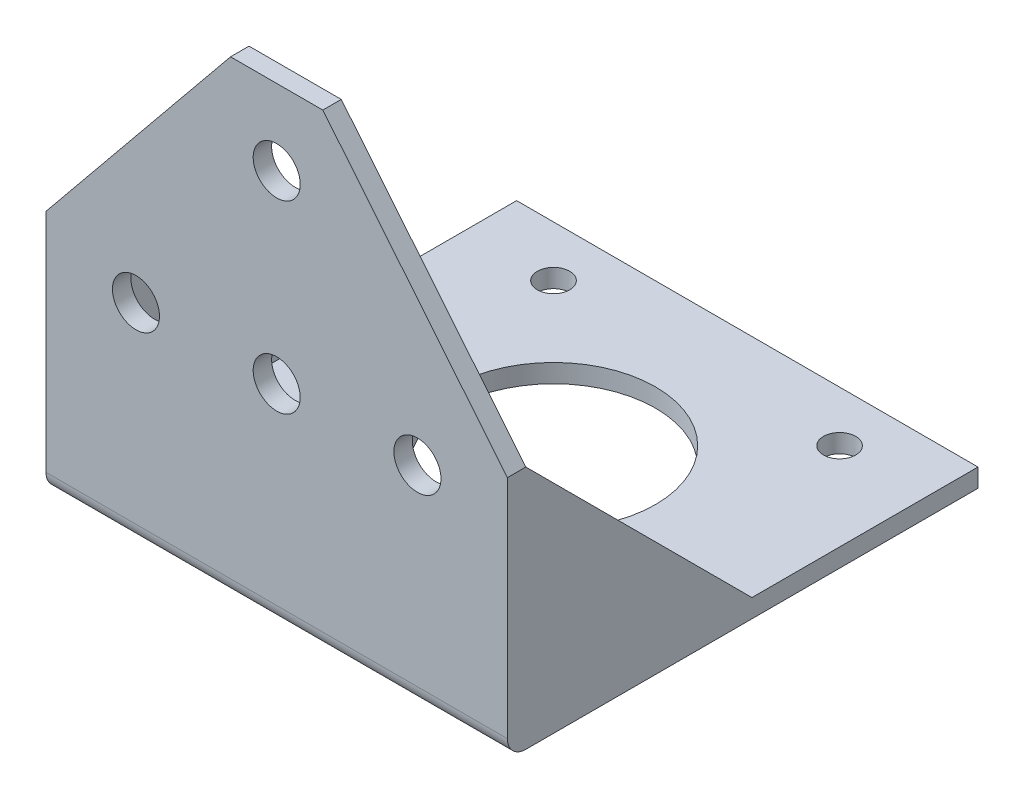
SolidWorks part; units mm, degrees
ref_plane "Front Plane" through (0, 0, 0) normal (0, 0, 1) x (1, 0, 0)
ref_plane "Top Plane" through (0, 0, 0) normal (0, 1, 0) x (1, 0, 0)
ref_plane "Right Plane" through (0, 0, 0) normal (1, 0, 0) x (0, 0, -1)
sketch "Sketch1" plane through (0, 0, 0) normal (0, 1, 0) x (1, 0, 0)
  line L0 (0, 0) -> (0, -30) construction
  line L2 (-25, 21) -> (25, 21)
  line L3 (-25, 21) -> (-25, -30)
  line L4 (-25, -30) -> (25, -30)
  line L5 (25, 21) -> (25, -30)
  line L6 (-25, 21) -> (25, -30) construction
  line L7 (-25, -30) -> (25, 21) construction
  point P2 (0, -4.5)
  dimension "D1" = 30
  dimension "D2" = 0
  dimension "D3" = 51
  dimension "D4" = 50
extrude "Boss-Extrude1" add sketch "Sketch1" along normal blind 2
sketch "Sketch2" plane through (0, 2, 0) normal (0, 1, 0) x (1, 0, 0)
  line L1 (0, 21) -> (0, -30) construction
  line L2 (25, 21) -> (-25, 21) construction
  line L3 (-25, -30) -> (25, -30) construction
  circle A0 centre (0, 0) radius 11.05
  circle A1 centre (-15.5, 15.5) radius 1.75
  circle A2 centre (-15.5, -15.5) radius 1.75
  circle A3 centre (15.5, -15.5) radius 1.75
  circle A4 centre (15.5, 15.5) radius 1.75
  dimension "D1" = 22.1
  dimension "D2" = 15.5
  dimension "D3" = 15.5
  dimension "D4" = 3.5
  dimension "D5" = 15.5
  dimension "D6" = 15.5
  dimension "D7" = 3.5
extrude "Cut-Extrude1" cut sketch "Sketch2" against normal blind 3
sketch "Sketch4" plane through (0, 2, 0) normal (0, 1, 0) x (1, 0, 0)
  line L0 (25, -30) -> (25, 21) construction
  line L1 (-25, -30) -> (25, -30)
  line L2 (-25, -30) -> (-25, -28)
  line L3 (-25, -28) -> (25, -28)
  line L4 (25, -30) -> (25, -28)
  dimension "D1" = 2
extrude "Boss-Extrude2" add sketch "Sketch4" along normal blind 49
sketch "Sketch5" plane through (25, 0, 0) normal (1, 0, 0) x (0, 0, -1)
  line L0 (-28, 26.5) -> (-3.5, 2)
  line L1 (-28, 51) -> (-28, 2) construction
  line L2 (-28, 2) -> (21, 2) construction
  line L3 (-3.5, 2) -> (-28, 2)
  line L4 (-28, 2) -> (-28, 26.5)
extrude "Boss-Extrude3" add sketch "Sketch5" against normal blind 2
sketch "Sketch6" plane through (-25, 0, 0) normal (-1, 0, 0) x (0, 0, 1)
  line L0 (28, 26.5) -> (3.5, 2)
  line L1 (28, 51) -> (28, 2) construction
  line L2 (-21, 2) -> (28, 2) construction
  line L3 (3.5, 2) -> (28, 2)
  line L4 (28, 2) -> (28, 26.5)
extrude "Boss-Extrude4" add sketch "Sketch6" against normal blind 2
sketch "Sketch7" plane through (0, 0, 28) normal (0, 0, -1) x (-1, 0, 0)
  line L0 (0, 51) -> (0, 2) construction
  line L1 (-25, 51) -> (25, 51) construction
  line L2 (-23, 2) -> (23, 2) construction
  line L3 (25, 42.8) -> (-25, 42.8) construction
  line L4 (25, 51) -> (25, 26.5) construction
  line L5 (-25, 51) -> (-25, 26.5) construction
  line L6 (25, 22.8) -> (-25, 22.8) construction
  line L7 (15.25, 51) -> (15.25, 22.8) construction
  circle A2 centre (0, 22.8) radius 2.55
  circle A3 centre (0, 42.8) radius 2.55
  circle A6 centre (15.25, 22.8) radius 2.55
  circle A7 centre (15.25, 42.8) radius 2.55
  circle A8 centre (-15.25, 42.8) radius 2.55
  circle A9 centre (-15.25, 22.8) radius 2.55
  dimension "D3" = 5.1
  dimension "D4" = 5.1
  dimension "D6" = 5.1
  dimension "D7" = 8.2
  dimension "D8" = 5.1
  dimension "D1" = 8.2
  dimension "D2" = 28.2
  dimension "D5" = 9.75
extrude "Cut-Extrude2" cut sketch "Sketch7" against normal blind 2
fillet "Fillet1" radius 2 2 edges at (0, 0, 30) (0, 2, 28)
sketch "Sketch8" plane through (0, 0, 28) normal (0, 0, -1) x (-1, 0, 0)
  line L0 (0, 51) -> (5, 51)
  line L1 (-25, 51) -> (25, 51) construction
  line L2 (5, 51) -> (25, 26.5)
  line L3 (0, 51) -> (-5, 51)
  line L4 (-5, 51) -> (-25, 26.5)
  line L6 (25, 26.5) -> (25, 51)
  line L7 (25, 51) -> (5, 51)
  line L8 (-5, 51) -> (-25, 51)
  line L9 (-25, 51) -> (-25, 26.5)
  circle M3 centre (-15.25, 42.8) radius 2.55
  circle M4 centre (15.25, 42.8) radius 2.55
  line M13 (25, 26.5) -> (25, 51)
  line M14 (25, 51) -> (-25, 51)
  line M15 (-25, 51) -> (-25, 26.5)
  dimension "D1" = 5
  dimension "D2" = 5
extrude "Cut-Extrude4" cut sketch "Sketch8" against normal blind 2 contours L2 M14 M13 M4 | L4 M14 M15 M3
